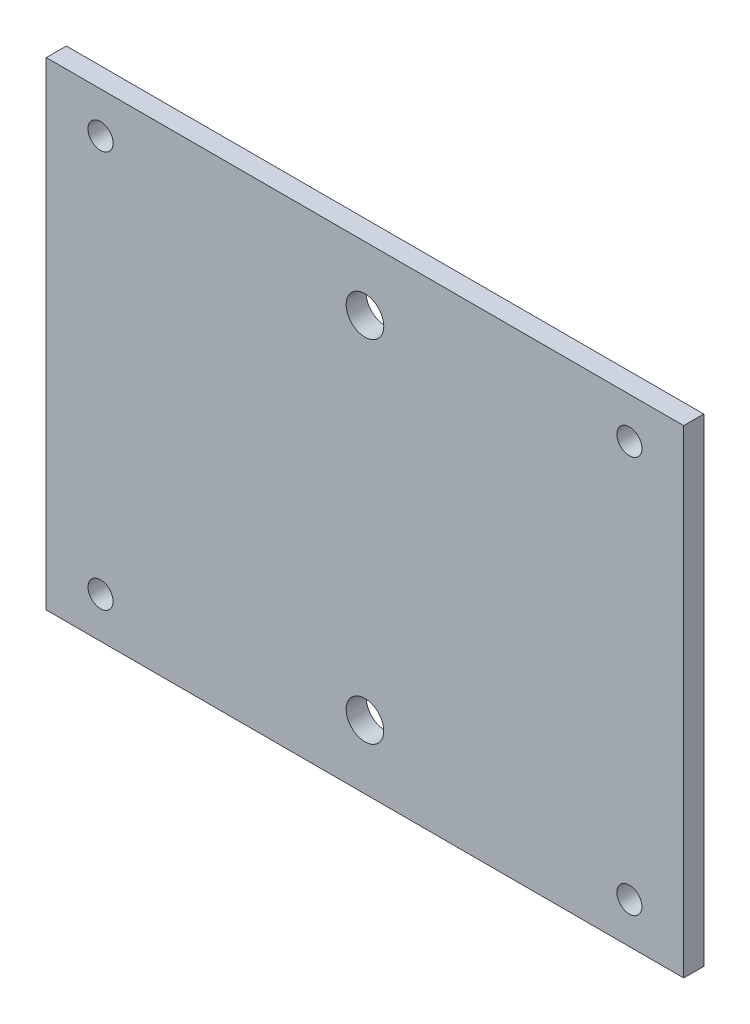
SolidWorks part; units mm, degrees
ref_plane "Front Plane" through (0, 0, 0) normal (0, 0, 1) x (1, 0, 0)
ref_plane "Top Plane" through (0, 0, 0) normal (0, 1, 0) x (1, 0, 0)
ref_plane "Right Plane" through (0, 0, 0) normal (1, 0, 0) x (0, 0, -1)
sketch "Sketch1" plane through (0, 0, 0) normal (0, 0, 1) x (1, 0, 0)
  line L0 (0, -40.427) -> (0, 40.427) construction
  line L1 (-25.42, -19.075) -> (25.42, -19.075)
  line L2 (-25.42, -19.075) -> (-25.42, 19.075)
  line L3 (-25.42, 19.075) -> (25.42, 19.075)
  line L4 (25.42, -19.075) -> (25.42, 19.075)
  line L5 (-25.42, -19.075) -> (25.42, 19.075) construction
  line L6 (-25.42, 19.075) -> (25.42, -19.075) construction
  line L7 (-52.9839, 0) -> (52.9839, 0) construction
  circle A0 centre (0, 13.975) radius 1.5
  circle A1 centre (0, -13.975) radius 1.5
  circle A2 centre (-21.0889, 15.825) radius 1
  circle A3 centre (21.0889, 15.825) radius 1
  circle A4 centre (21.0889, -15.825) radius 1
  circle A5 centre (-21.0889, -15.825) radius 1
  point P0 (0, 0)
  point P9 (0, 0)
  point P14 (0, 0)
  dimension "D3" = 3
  dimension "D4" = 5.1
  dimension "D5" = 2
  dimension "D1" = 50.84
  dimension "D2" = 38.15
  dimension "D6" = 3.25
extrude "Boss-Extrude1" add sketch "Sketch1" along normal blind 1.6
